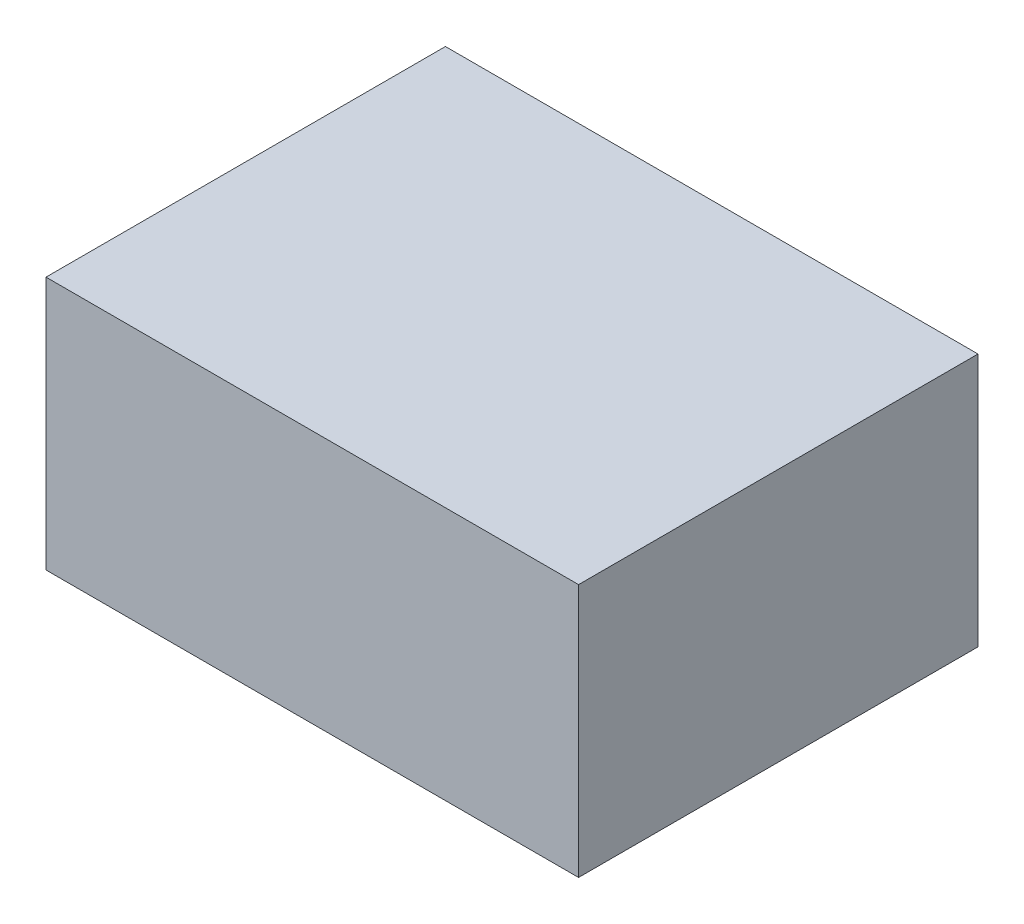
SolidWorks part; units mm, degrees
ref_plane "Front Plane" through (0, 0, 0) normal (0, 0, 1) x (1, 0, 0)
ref_plane "Top Plane" through (0, 0, 0) normal (0, 1, 0) x (1, 0, 0)
ref_plane "Right Plane" through (0, 0, 0) normal (1, 0, 0) x (0, 0, -1)
sketch "Sketch1" plane through (0, 0, 0) normal (0, 1, 0) x (1, 0, 0)
  line L1 (80, 60) -> (-80, 60)
  line L2 (80, 60) -> (80, -60)
  line L3 (80, -60) -> (-80, -60)
  line L4 (-80, 60) -> (-80, -60)
  line L5 (0, -60) -> (0, 60) construction
  line L6 (80, 0) -> (-80, 0) construction
  point P0 (0, 0)
  dimension "D1" = 120
  dimension "D2" = 160
extrude "Boss-Extrude1" add sketch "Sketch1" along normal blind 76.2
